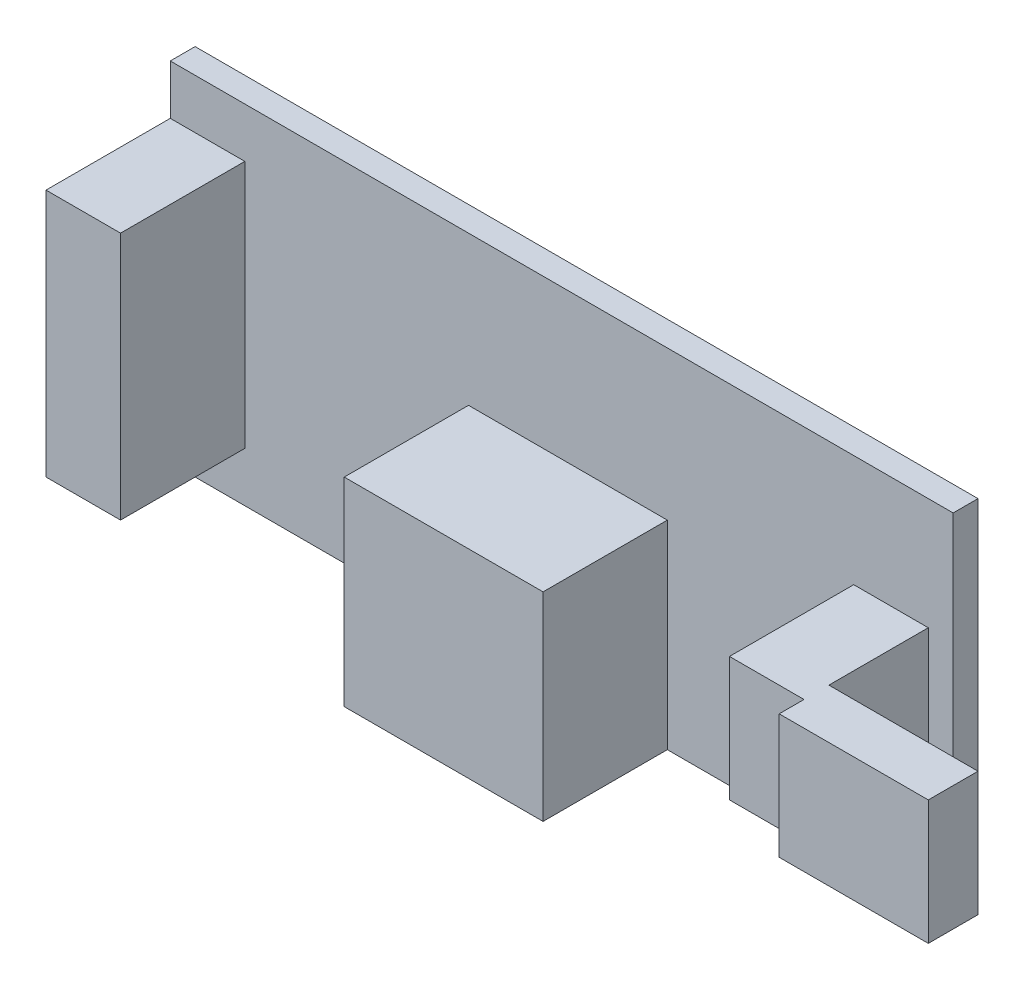
SolidWorks part; units mm, degrees
ref_plane "Plan de face" through (0, 0, 0) normal (0, 0, 1) x (1, 0, 0)
ref_plane "Plan de dessus" through (0, 0, 0) normal (0, 1, 0) x (1, 0, 0)
ref_plane "Plan de droite" through (0, 0, 0) normal (1, 0, 0) x (0, 0, -1)
sketch "Esquisse1" plane through (0, 0, 0) normal (0, 0, 1) x (1, 0, 0)
  line L5 (-19.1758, 8.0883) -> (12.3242, 8.0883)
  line L6 (-19.1758, 8.0883) -> (-19.1758, -5.9117)
  line L7 (-19.1758, -5.9117) -> (12.3242, -5.9117)
  line L8 (12.3242, 8.0883) -> (12.3242, -5.9117)
  dimension "D2" = 31.5
  dimension "14.2" = 14
extrude "Boss.-Extru.1" add sketch "Esquisse1" against normal blind 1
sketch "Esquisse2" plane through (0, 0, 0) normal (0, 0, 1) x (1, 0, 0)
  line L0 (-19.1758, 8.0883) -> (-19.1758, -5.9117) construction
  line L1 (-7.1758, 2.0883) -> (0.8242, 2.0883)
  line L2 (-7.1758, 2.0883) -> (-7.1758, -5.9117)
  line L3 (-7.1758, -5.9117) -> (0.8242, -5.9117)
  line L4 (0.8242, 2.0883) -> (0.8242, -5.9117)
  line L5 (-19.1758, -5.9117) -> (12.3242, -5.9117) construction
  dimension "D1" = 12
  dimension "D2" = 20
  dimension "D3" = 8
  dimension "D4" = 0
extrude "Boss.-Extru.2" add sketch "Esquisse2" along normal blind 5
sketch "Esquisse3" plane through (0, 0, 0) normal (0, 0, 1) x (1, 0, 0)
  line L0 (0.8242, -5.9117) -> (12.3242, -5.9117) construction
  line L1 (8.3242, 3.5883) -> (11.3242, 3.5883)
  line L2 (8.3242, 3.5883) -> (8.3242, -1.4117)
  line L3 (8.3242, -1.4117) -> (11.3242, -1.4117)
  line L4 (11.3242, 3.5883) -> (11.3242, -1.4117)
  line L5 (12.3242, -5.9117) -> (12.3242, 8.0883) construction
  point P6 (9.8242, 3.5883)
  dimension "D1" = 4.5
  dimension "D2" = 9.5
  dimension "D3" = 1
  dimension "D4" = 4
extrude "Boss.-Extru.3" add sketch "Esquisse3" along normal blind 5
sketch "Esquisse4" plane through (0, 0, 0) normal (0, 0, 1) x (1, 0, 0)
  line L0 (12.3242, 8.0883) -> (-19.1758, 8.0883) construction
  line L1 (-19.1758, 6.0883) -> (-16.1758, 6.0883)
  line L2 (-19.1758, 6.0883) -> (-19.1758, -3.9117)
  line L3 (-19.1758, -3.9117) -> (-16.1758, -3.9117)
  line L4 (-16.1758, 6.0883) -> (-16.1758, -3.9117)
  line L6 (-19.1758, 8.0883) -> (-19.1758, -5.9117) construction
  dimension "D1" = 2
  dimension "D2" = 12
  dimension "D3" = 0
  dimension "D4" = 3
extrude "Boss.-Extru.4" add sketch "Esquisse4" along normal blind 5
sketch "Esquisse6" plane through (11.3242, 0, 0) normal (1, 0, 0) x (0, 0, -1)
  line L0 (-5, 3.5883) -> (0, 3.5883) construction
  line L3 (-4, 2.9926) -> (-4, -0.9171) construction
  line L6 (-4, 3.5883) -> (-6, 3.5883)
  line L7 (-4, 3.5883) -> (-4, -1.4117)
  line L8 (-4, -1.4117) -> (-6, -1.4117)
  line L9 (-6, 3.5883) -> (-6, -1.4117)
extrude "Boss.-Extru.6" add sketch "Esquisse6" along normal blind 6
